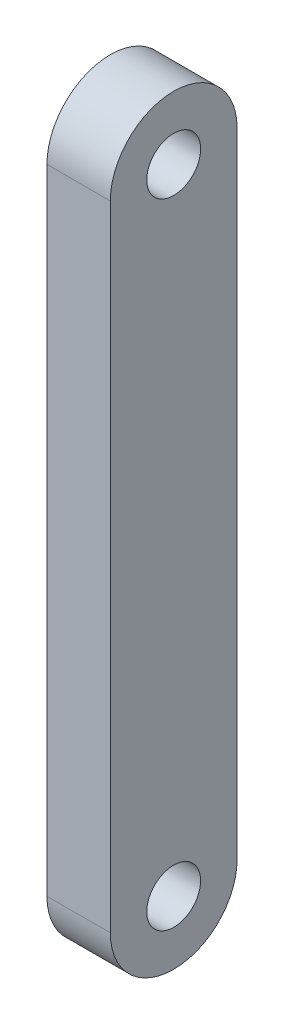
SolidWorks part; units mm, degrees
material "ABS"
ref_plane "Alzado" through (0, 0, 0) normal (0, 0, 1) x (1, 0, 0)
ref_plane "Planta" through (0, 0, 0) normal (0, 1, 0) x (1, 0, 0)
ref_plane "Vista lateral" through (0, 0, 0) normal (1, 0, 0) x (0, 0, -1)
sketch "Croquis1" plane through (0, 0, 0) normal (1, 0, 0) x (0, 0, -1)
  line L0 (0, -50) -> (0, 50) construction
  line L1 (-10, -50) -> (-10, 50)
  line L2 (10, -50) -> (10, 50)
  arc A0 (-10, -50) -> (10, -50) centre (0, -50) ccw
  arc A1 (10, 50) -> (-10, 50) centre (0, 50) ccw
  circle A2 centre (0, 50) radius 4.25
  circle A3 centre (0, -50) radius 4.25
  point P2 (0, 0)
  dimension "D2" = 8.5
  dimension "D1" = 100
  dimension "D3" = 20
extrude "Saliente-Extruir1" add sketch "Croquis1" along normal mid plane 10
